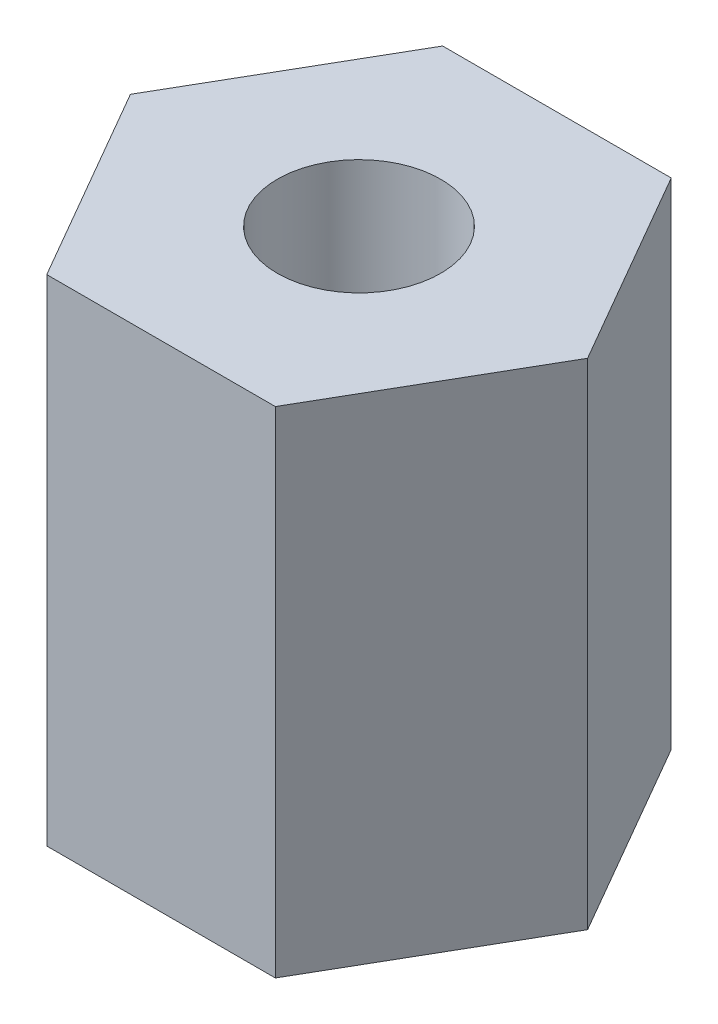
SolidWorks part; units mm, degrees
material "黄铜"
ref_plane "前视基准面" through (0, 0, 0) normal (0, 0, 1) x (1, 0, 0)
ref_plane "上视基准面" through (0, 0, 0) normal (0, 1, 0) x (1, 0, 0)
ref_plane "右视基准面" through (0, 0, 0) normal (1, 0, 0) x (0, 0, -1)
other "Configuration Table"
sketch "草图1" plane through (0, 0, 0) normal (0, 1, 0) x (1, 0, 0)
  line L1 (2.3094, 4) -> (-2.3094, 4)
  line L2 (-2.3094, 4) -> (-4.6188, 0)
  line L3 (-4.6188, 0) -> (-2.3094, -4)
  line L4 (-2.3094, -4) -> (2.3094, -4)
  line L5 (2.3094, -4) -> (4.6188, 0)
  line L6 (4.6188, 0) -> (2.3094, 4)
  circle A0 centre (0, 0) radius 4 construction
  dimension "D1" = 8
extrude "凸台-拉伸1" add sketch "草图1" along normal blind 10
hole_wizard "M4 螺纹孔1" positions "草图2" profile "草图3" tap size "M4" standard "GB"
sketch "草图2" plane through (0, 10, 0) normal (0, 1, 0) x (1, 0, 0)
  point P0 (0, 0)
sketch "草图3" plane through (0, 10, 0) normal (1, 0, 0) x (0, 0, 1)
  line L0 (0, 0) -> (0, 15.0914)
  line L1 (0, 15.0914) -> (1.65, 14.1)
  line L2 (1.65, 14.1) -> (1.65, 0)
  line L5 (1.65, 0) -> (0, 0)
  line L10 (0, 15.0914) -> (-1.65, 14.1) construction
  line L11 (0, -6.35) -> (0, 107.95) construction
  dimension "螺纹孔钻头直径" = 3.3
  dimension "螺纹孔钻头深度" = 14.1
  dimension "导头角度" = 118
